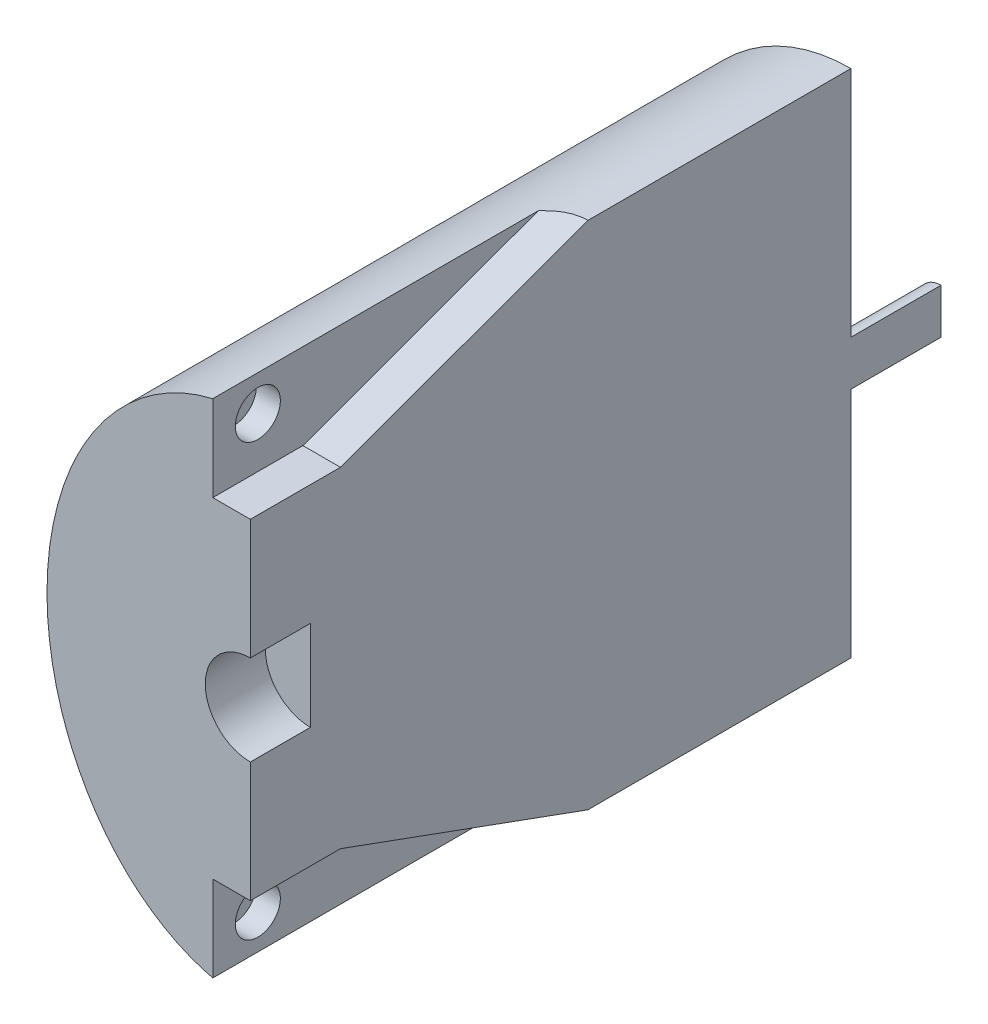
SolidWorks part; units mm, degrees
ref_plane "Alzado" through (0, 0, 0) normal (0, 0, 1) x (1, 0, 0)
ref_plane "Planta" through (0, 0, 0) normal (0, 1, 0) x (1, 0, 0)
ref_plane "Vista lateral" through (0, 0, 0) normal (1, 0, 0) x (0, 0, -1)
sketch "Croquis1" plane through (0, 0, 0) normal (0, 0, 1) x (1, 0, 0)
  ellipse E0 centre (-119.0676, 97.1607) end of major axis (-119.0676, 182.1607) minor radius 67.731
extrude "Saliente-Extruir1" add sketch "Croquis1" along normal blind 200
sketch "Croquis3" plane through (0, 0, 200) normal (0, 0, 1) x (1, 0, 0)
  line L3 (-119.0676, 182.1607) -> (-119.0676, 12.1607) construction
  line L4 (-51.3365, 97.1599) -> (-186.7986, 97.1599) construction
  line L5 (-171.8299, 137.1599) -> (-171.8299, 57.1599)
  line L6 (-171.8299, 137.1599) -> (-178.8306, 137.1599)
  line L7 (-171.8299, 57.1599) -> (-178.8299, 57.1599)
  ellipse E1 centre (-119.0676, 97.1607) end of major axis (-119.0676, 182.1607) minor radius 67.731 construction
  ellipse E2 centre (-119.0676, 97.1607) end of major axis (-119.0676, 182.1607) minor radius 67.731 (-178.8306, 137.1599) -> (-178.8299, 57.1599) ccw
  dimension "D1" = 40
  dimension "D2" = 40
  dimension "D3" = 7
extrude "Cortar-Extruir1" cut sketch "Croquis3" against normal blind 100
sketch "Croquis4" plane through (0, 0, 200) normal (0, 0, 1) x (1, 0, 0)
  line L0 (-178.8306, 137.1599) -> (-171.8299, 137.1599)
  line L1 (-171.8299, 137.1599) -> (-171.8299, 57.1599)
  line L2 (-171.8299, 57.1599) -> (-178.8299, 57.1599)
  ellipse E0 centre (-119.0062, 97.0651) end of major axis (-118.77, 11.9697) minor radius 67.7787 (-178.8306, 137.1599) -> (-178.8299, 57.1599) ccw
  ellipse E1 centre (-119.0676, 97.1607) end of major axis (-119.0676, 182.1607) minor radius 67.731 (-178.8299, 57.1599) -> (-178.8306, 137.1599) ccw construction
extrude "Saliente-Extruir2" add sketch "Croquis4" against normal blind 30
sketch "Croquis5" plane through (0, 0, 0) normal (0, 0, -1) x (-1, 0, 0)
  circle A0 centre (119.0676, 97.1607) radius 7.5
  dimension "D1" = 15
extrude "Saliente-Extruir3" add sketch "Croquis5" along normal blind 30
sketch "Croquis7" plane through (0, 0, 200) normal (0, 0, 1) x (1, 0, 0)
  line L0 (-119.0676, 182.1607) -> (-119.0676, 12.1607) construction
  line L10 (-51.3365, 97.1607) -> (-186.7986, 97.1607) construction
  line L11 (-131.5676, 42.1607) -> (-106.5676, 42.1607)
  line L12 (-131.5676, 42.1607) -> (-131.5676, 13.6208)
  line L14 (-106.5676, 42.1607) -> (-106.5676, 13.6208)
  line L16 (-131.5676, 180.7006) -> (-131.5676, 152.1607)
  line L17 (-131.5676, 152.1607) -> (-106.5676, 152.1607)
  line L18 (-106.5676, 180.7006) -> (-106.5676, 152.1607)
  ellipse E0 centre (-119.0676, 97.1607) end of major axis (-119.0676, 12.1607) minor radius 67.731 (-131.5676, 13.6208) -> (-106.5676, 13.6208) ccw
  ellipse E2 centre (-119.0676, 97.1607) end of major axis (-119.0676, 182.1607) minor radius 67.731 (-178.8299, 57.1599) -> (-178.8306, 137.1599) ccw construction
  ellipse E3 centre (-119.0676, 97.1607) end of major axis (-119.0676, 12.1607) minor radius 67.731 (-106.5676, 180.7006) -> (-131.5676, 180.7006) ccw
  dimension "D1" = 25
  dimension "D2" = 12.5
  dimension "D3" = 30
  dimension "D4" = 25
  dimension "D5" = 12.5
  dimension "D6" = 30
extrude "Cortar-Extruir3" cut sketch "Croquis7" against normal blind 30
sketch "Croquis8" plane through (0, 0, 200) normal (0, 0, 1) x (1, 0, 0)
  line L1 (-119.0676, 202.4796) -> (-35.7683, 202.4796)
  line L2 (-119.0676, 202.4796) -> (-119.0676, -8.4995)
  line L3 (-119.0676, -8.4995) -> (-35.7683, -8.4995)
  line L4 (-35.7683, 202.4796) -> (-35.7683, -8.4995)
extrude "Cortar-Extruir4" cut sketch "Croquis8" against normal through all
sketch "Croquis9" plane through (0, 0, 200) normal (0, 0, 1) x (1, 0, 0)
  line L0 (-119.0676, 152.1607) -> (-119.0676, 42.1607) construction
  circle A1 centre (-119.0676, 97.1607) radius 15
  dimension "D1" = 30
extrude "Cortar-Extruir5" cut sketch "Croquis9" against normal blind 20
sketch "Croquis10" plane through (-131.5676, 0, 0) normal (1, 0, 0) x (0, 0, -1)
  circle A0 centre (-185, 168.9307) radius 7.5
  circle A1 centre (-185, 25.3908) radius 7.5
  dimension "D1" = 15
  dimension "D2" = 15
extrude "Cortar-Extruir6" cut sketch "Croquis10" against normal blind 8
sketch "Croquis11" plane through (-119.0676, 0, 0) normal (1, 0, 0) x (0, 0, -1)
  line L0 (-170, 42.1607) -> (-57.2369, 1.1183)
  line L1 (-57.2369, 1.1183) -> (-170, -2.4419)
  line L2 (-170, -2.4419) -> (-170, 42.1607)
  line L3 (-170, 152.1607) -> (-58.8192, 192.6272)
  line L4 (-58.8192, 192.6272) -> (-170, 211.0022)
  line L5 (-170, 211.0022) -> (-170, 152.1607)
  dimension "D1" = 70
  dimension "D2" = 120
  dimension "D3" = 70
extrude "Cortar-Extruir7" cut sketch "Croquis11" against normal blind 12.5
